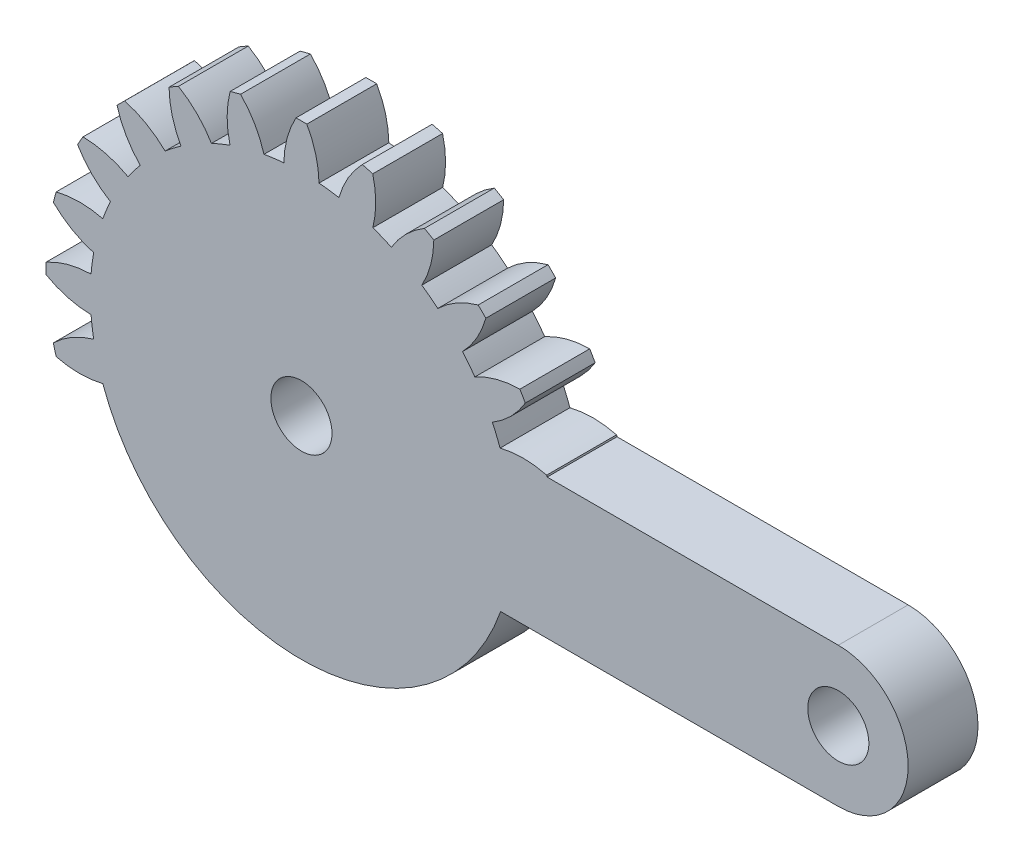
SolidWorks part; units mm, degrees
ref_plane "Front Plane" through (0, 0, 0) normal (0, 0, 1) x (1, 0, 0)
ref_plane "Top Plane" through (0, 0, 0) normal (0, 1, 0) x (1, 0, 0)
ref_plane "Right Plane" through (0, 0, 0) normal (1, 0, 0) x (0, 0, -1)
sketch "Sketch1" plane through (0, 0, 0) normal (0, 0, 1) x (1, 0, 0)
  line L0 (0, 0) -> (0, 14.63) construction
  line L1 (0, 0) -> (39.758, 0) construction
  line L2 (11.4091, 4) -> (30.75, 4)
  line L3 (30.75, -4) -> (11.4091, -4)
  circle A0 centre (0, 0) radius 12.09
  circle A1 centre (0, 0) radius 1.75
  circle A2 centre (0, 0) radius 14.63
  arc A3 (-0.31, 14.6267) -> (-1.0062, 12.0481) centre (4.3933, 11.9736) ccw
  arc A4 (0.31, 14.6267) -> (1.0062, 12.0481) centre (-4.3933, 11.9736) cw
  arc A5 (4.0851, 14.0481) -> (4.0902, 11.3771) centre (-1.1446, 12.7027) cw
  arc A6 (3.4862, 14.2086) -> (2.1464, 11.898) centre (7.3426, 10.4285) ccw
  arc A7 (7.5818, 12.5121) -> (6.8954, 9.9308) centre (2.1821, 12.5661) cw
  arc A8 (7.0449, 12.8221) -> (5.1526, 10.937) centre (9.7915, 8.1728) ccw
  arc A9 (10.5619, 10.1234) -> (9.2308, 7.8078) centre (5.3601, 11.5731) cw
  arc A10 (10.1234, 10.5619) -> (7.8078, 9.2308) centre (11.5731, 5.3601) ccw
  arc A11 (12.8221, 7.0449) -> (10.937, 5.1526) centre (8.1728, 9.7915) cw
  arc A12 (12.5121, 7.5818) -> (9.9308, 6.8954) centre (12.5661, 2.1821) ccw
  arc A13 (14.2086, 3.4862) -> (11.898, 2.1464) centre (10.4285, 7.3426) cw
  arc A14 (14.0481, 4.0851) -> (11.3771, 4.0902) centre (12.7027, -1.1446) ccw
  arc A15 (14.6267, -0.31) -> (12.0481, -1.0062) centre (11.9736, 4.3933) cw
  arc A16 (14.6267, 0.31) -> (12.0481, 1.0062) centre (11.9736, -4.3933) ccw
  arc A17 (14.0481, -4.0851) -> (11.3771, -4.0902) centre (12.7027, 1.1446) cw
  arc A18 (14.2086, -3.4862) -> (11.898, -2.1464) centre (10.4285, -7.3426) ccw
  arc A19 (12.5121, -7.5818) -> (9.9308, -6.8954) centre (12.5661, -2.1821) cw
  arc A20 (12.8221, -7.0449) -> (10.937, -5.1526) centre (8.1728, -9.7915) ccw
  arc A21 (10.1234, -10.5619) -> (7.8078, -9.2308) centre (11.5731, -5.3601) cw
  arc A22 (10.5619, -10.1234) -> (9.2308, -7.8078) centre (5.3601, -11.5731) ccw
  arc A23 (7.0449, -12.8221) -> (5.1526, -10.937) centre (9.7915, -8.1728) cw
  arc A24 (7.5818, -12.5121) -> (6.8954, -9.9308) centre (2.1821, -12.5661) ccw
  arc A25 (3.4862, -14.2086) -> (2.1464, -11.898) centre (7.3426, -10.4285) cw
  arc A26 (4.0851, -14.0481) -> (4.0902, -11.3771) centre (-1.1446, -12.7027) ccw
  arc A27 (-0.31, -14.6267) -> (-1.0062, -12.0481) centre (4.3933, -11.9736) cw
  arc A28 (0.31, -14.6267) -> (1.0062, -12.0481) centre (-4.3933, -11.9736) ccw
  arc A29 (-4.0851, -14.0481) -> (-4.0902, -11.3771) centre (1.1446, -12.7027) cw
  arc A30 (-3.4862, -14.2086) -> (-2.1464, -11.898) centre (-7.3426, -10.4285) ccw
  arc A31 (-7.5818, -12.5121) -> (-6.8954, -9.9308) centre (-2.1821, -12.5661) cw
  arc A32 (-7.0449, -12.8221) -> (-5.1526, -10.937) centre (-9.7915, -8.1728) ccw
  arc A33 (-10.5619, -10.1234) -> (-9.2308, -7.8078) centre (-5.3601, -11.5731) cw
  arc A34 (-10.1234, -10.5619) -> (-7.8078, -9.2308) centre (-11.5731, -5.3601) ccw
  arc A35 (-12.8221, -7.0449) -> (-10.937, -5.1526) centre (-8.1728, -9.7915) cw
  arc A36 (-12.5121, -7.5818) -> (-9.9308, -6.8954) centre (-12.5661, -2.1821) ccw
  arc A37 (-14.2086, -3.4862) -> (-11.898, -2.1464) centre (-10.4285, -7.3426) cw
  arc A38 (-14.0481, -4.0851) -> (-11.3771, -4.0902) centre (-12.7027, 1.1446) ccw
  arc A39 (-14.6267, 0.31) -> (-12.0481, 1.0062) centre (-11.9736, -4.3933) cw
  arc A40 (-14.6267, -0.31) -> (-12.0481, -1.0062) centre (-11.9736, 4.3933) ccw
  arc A41 (-14.0481, 4.0851) -> (-11.3771, 4.0902) centre (-12.7027, -1.1446) cw
  arc A42 (-14.2086, 3.4862) -> (-11.898, 2.1464) centre (-10.4285, 7.3426) ccw
  arc A43 (-12.5121, 7.5818) -> (-9.9308, 6.8954) centre (-12.5661, 2.1821) cw
  arc A44 (-12.8221, 7.0449) -> (-10.937, 5.1526) centre (-8.1728, 9.7915) ccw
  arc A45 (-10.1234, 10.5619) -> (-7.8078, 9.2308) centre (-11.5731, 5.3601) cw
  arc A46 (-10.5619, 10.1234) -> (-9.2308, 7.8078) centre (-5.3601, 11.5731) ccw
  arc A47 (-7.0449, 12.8221) -> (-5.1526, 10.937) centre (-9.7915, 8.1728) cw
  arc A48 (-7.5818, 12.5121) -> (-6.8954, 9.9308) centre (-2.1821, 12.5661) ccw
  arc A49 (-3.4862, 14.2086) -> (-2.1464, 11.898) centre (-7.3426, 10.4285) cw
  arc A50 (-4.0851, 14.0481) -> (-4.0902, 11.3771) centre (1.1446, 12.7027) ccw
  arc A51 (30.75, 4) -> (30.75, -4) centre (30.75, 0) cw
  circle A52 centre (30.75, 0) radius 1.75
  point P153 (0, 0)
  dimension "D1" = 3.5
  dimension "D2" = 24.18
  dimension "D3" = 29.26
  dimension "D6" = 5.4
  dimension "D8" = 30.75
  dimension "D9" = 4
  dimension "D10" = 3.5
  dimension "D4" = 0.62
  dimension "D11" = 1.15
  dimension "D7" = 24
extrude "Boss-Extrude1" add sketch "Sketch1" along normal blind 4 contours A51 L2 A2 L3 A52 | A2 A18 A0 L3 | A18 A2 A15 A0 | A2 A16 A0 A15 | A16 A2 A13 A0 | A13 A2 L2 A0 | A2 A14 A0 L2 | A2 A12 A0 A11 | A2 A10 A0 A9 | A2 A8 A0 A7 | A2 A6 A0 A5 | A4 A2 A3 A0 | A2 A50 A0 A49 | A2 A48 A0 A47 | A2 A46 A0 A45 | A2 A44 A0 A43 | A2 A42 A0 A41 | A2 A40 A0 A39 | A2 A38 A0 A37 | A0 L3
